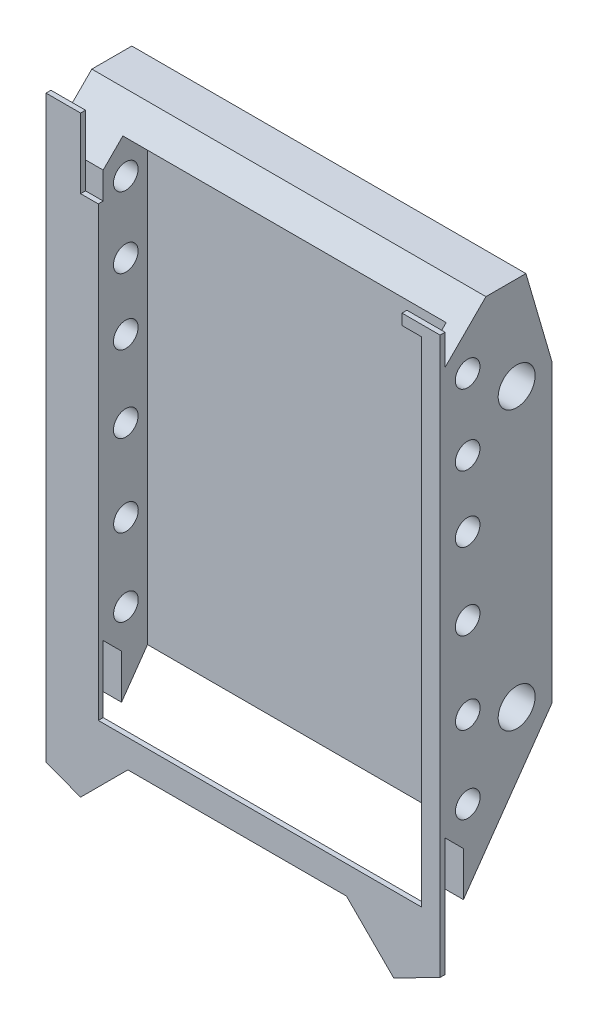
SolidWorks part; units mm, degrees
ref_plane "Front Plane" through (0, 0, 0) normal (0, 0, 1) x (1, 0, 0)
ref_plane "Top Plane" through (0, 0, 0) normal (0, 1, 0) x (1, 0, 0)
ref_plane "Right Plane" through (0, 0, 0) normal (1, 0, 0) x (0, 0, -1)
sketch "Sketch1" plane through (0, 0, 0) normal (0, 0, 1) x (1, 0, 0)
  line L0 (-154.8975, 156.3985) -> (-154.8975, 192.4096)
  line L1 (-137.0763, 156.3985) -> (28.6365, 156.3985)
  line L2 (-154.8975, 156.3985) -> (-154.8975, -46.8015)
  line L3 (-154.8975, -46.8015) -> (48.3025, -46.8015)
  line L4 (48.3025, 156.3985) -> (48.3025, -46.8015)
  line L5 (-154.8975, 192.4096) -> (-137.0763, 192.4096)
  line L6 (-137.0763, 192.4096) -> (-137.0763, 156.3985)
  line L7 (-137.0763, 156.3985) -> (28.6365, 156.3985)
  line L8 (48.3025, 185.9428) -> (28.6365, 185.9428)
  line L9 (28.6365, 185.9428) -> (28.6365, 156.3985)
  line L10 (48.3025, 185.9428) -> (48.3025, 156.3985)
  line L11 (-154.8975, -46.8015) -> (-154.8975, -106.3789)
  line L12 (-137.0763, -113.088) -> (-154.8975, -106.3789)
  line L13 (-137.0763, -113.088) -> (-112.6916, -88.7033)
  line L14 (-112.6916, -88.7033) -> (0, -88.7033)
  line L15 (0, -88.7033) -> (24.3847, -113.088)
  line L16 (24.3847, -113.088) -> (48.3025, -100.8956)
  line L17 (48.3025, -100.8956) -> (48.3025, -46.8015)
  line L18 (48.3025, -46.8015) -> (46.832, -45.0393)
  dimension "D1" = 203.2
  dimension "D2" = 203.2
extrude "Boss-Extrude1" add sketch "Sketch1" along normal blind 2.54
sketch "Sketch2" plane through (48.3025, 0, 0) normal (1, 0, 0) x (0, 0, -1)
  line L0 (0, 170.2346) -> (21.0754, 191.31)
  line L1 (0, 111.76) -> (0, -111.76) construction
  line L2 (21.0754, 191.31) -> (41.6951, 191.31)
  line L3 (41.6951, 191.31) -> (55.1363, 145.1915)
  line L4 (55.1363, 145.1915) -> (55.1363, -7.2085)
  line L5 (55.1363, -7.2085) -> (9.4647, -72.142)
  line L6 (9.4647, -72.142) -> (9.4647, -49.3062)
  line L7 (9.4647, -49.3062) -> (0, -39.8415)
  line L8 (0, 170.2346) -> (0, -39.8415)
  dimension "D1" = 152.4
extrude "Boss-Extrude2" add sketch "Sketch2" against normal up to surface (203.2 mm away) up to face at (-154.8975, 43.0153, 1.27)
sketch "Sketch3" plane through (48.3025, 0, 0) normal (1, 0, 0) x (0, 0, -1)
  line L0 (31.7219, 0) -> (-31.7219, 0) construction
  circle A0 centre (36.9337, 143.349) radius 9.525
  circle A1 centre (36.9337, 0) radius 9.525
  dimension "D1" = 19.05
extrude "Cut-Extrude1" cut sketch "Sketch3" against normal through all
sketch "Sketch4" plane through (48.3025, 0, 0) normal (1, 0, 0) x (0, 0, -1)
  circle A0 centre (11.6501, 161.7212) radius 6.35
  circle A1 centre (11.7366, 9.3212) radius 6.35
  circle A2 centre (11.6501, 125.1607) radius 6.35
  circle A3 centre (11.6501, 91.0644) radius 6.35
  circle A4 centre (11.6501, 51.5436) radius 6.35
  circle A5 centre (11.7366, -30.5975) radius 6.35
  dimension "D1" = 12.7
  dimension "D2" = 152.4
extrude "Cut-Extrude2" cut sketch "Sketch4" against normal through all
sketch "Sketch5" plane through (0, 0, 2.54) normal (0, 0, 1) x (1, 0, 0)
  line L1 (-127.9649, 180.3909) -> (38.7364, 180.3909)
  line L2 (-127.9649, 180.3909) -> (-127.9649, -74.2434)
  line L3 (-127.9649, -74.2434) -> (38.7364, -74.2434)
  line L4 (38.7364, 180.3909) -> (38.7364, -74.2434)
extrude "Cut-Extrude3" cut sketch "Sketch5" against normal blind 25.4
